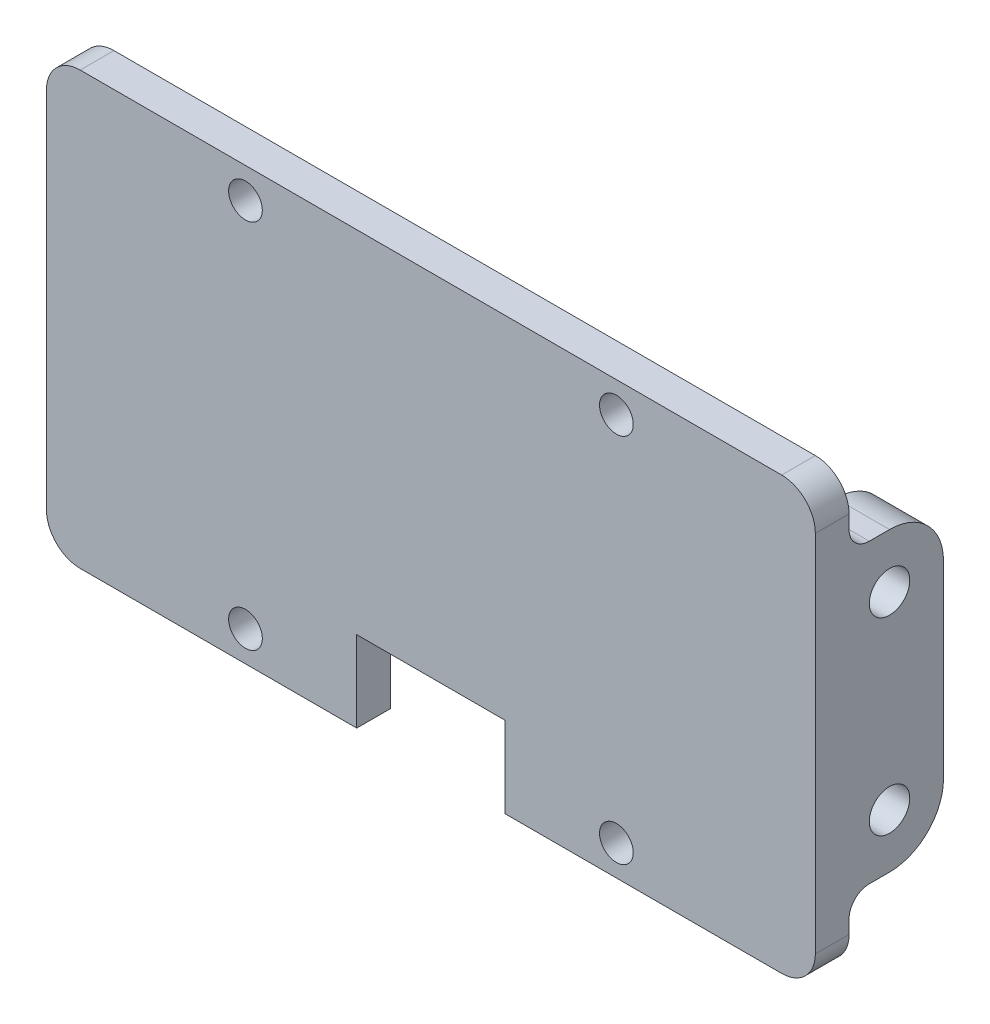
SolidWorks part; units mm, degrees
ref_plane "前视基准面" through (0, 0, 0) normal (0, 0, 1) x (1, 0, 0)
ref_plane "上视基准面" through (0, 0, 0) normal (0, 1, 0) x (1, 0, 0)
ref_plane "右视基准面" through (0, 0, 0) normal (1, 0, 0) x (0, 0, -1)
sketch "草图1" plane through (0, 0, 0) normal (0, 0, 1) x (1, 0, 0)
  line L1 (-16, -16) -> (16, -16)
  line L3 (-16, 16) -> (16, 16)
  line L13 (0, -10) -> (5.5, -10)
  line L14 (5.5, -10) -> (5.5, -16)
  line L15 (5.5, -16) -> (-5.5, -16)
  line L16 (-5.5, -16) -> (-5.5, -10)
  line L17 (-5.5, -10) -> (0, -10)
  line L18 (-28.5, -16) -> (28.5, -16)
  line L19 (-28.5, -16) -> (-28.5, 16)
  line L20 (-28.5, 16) -> (28.5, 16)
  line L21 (28.5, -16) -> (28.5, 16)
  circle A0 centre (-13.75, 13.75) radius 1.25
  circle A1 centre (13.75, 13.75) radius 1.25
  circle A2 centre (-13.75, -13.75) radius 1.25
  circle A3 centre (13.75, -13.75) radius 1.25
  point P0 (0, 0)
  point P6 (0, 0)
  point P15 (0, 0)
extrude "凸台-拉伸1" add sketch "草图1" along normal blind 2.5
sketch "草图3" plane through (-28.5, 0, 0) normal (-1, 0, 0) x (0, 0, 1)
  line L2 (0, -16) -> (0, 16) construction
  line L8 (-3, 11) -> (0, 11)
  line L10 (-7, -7) -> (-7, 7)
  line L11 (-3, -11) -> (0, -11)
  line L12 (0, -11) -> (0, 11)
  circle A0 centre (-3, 7) radius 1.5
  circle A1 centre (-3, -7) radius 1.5
  arc A4 (-7, 7) -> (-3, 11) centre (-3, 7) cw
  arc A5 (-7, -7) -> (-3, -11) centre (-3, -7) ccw
extrude "凸台-拉伸2" add sketch "草图3" against normal blind 4
sketch "草图4" plane through (28.5, 0, 0) normal (1, 0, 0) x (0, 0, -1)
  line L16 (7, -7) -> (7, 7)
  line L17 (3, 11) -> (0, 11)
  line L18 (0, 11) -> (0, -11)
  line L19 (0, -11) -> (3, -11)
  line L20 (7, -7) -> (7, 7)
  line L21 (3, 11) -> (0, 11)
  line L22 (0, 11) -> (0, -11)
  line L23 (0, -11) -> (3, -11)
  circle A9 centre (3, 7) radius 1.5
  circle A10 centre (3, 7) radius 1.5
  circle A11 centre (3, -7) radius 1.5
  circle A12 centre (3, -7) radius 1.5
  arc A14 (3, -11) -> (7, -7) centre (3, -7) ccw
  arc A15 (7, 7) -> (3, 11) centre (3, 7) ccw
  arc A16 (3, -11) -> (7, -7) centre (3, -7) ccw
  arc A17 (7, 7) -> (3, 11) centre (3, 7) ccw
  point P9 (0, 0)
  dimension "D1" = 0
  dimension "D2" = 0
  dimension "D3" = 0
extrude "凸台-拉伸3" add sketch "草图4" against normal blind 4
fillet "圆角2" radius 2.5 4 edges at (-28.5, -16, 1.25) (28.5, -16, 1.25) (-28.5, 16, 1.25) (28.5, 16, 1.25)
fillet "圆角3" radius 1.5 4 edges at (26.5, 11, 0) (26.5, -11, 0) (-26.5, -11, 0) (-26.5, 11, 0)
other "角撑板1" parameters "D1"=5, "D2"=5, "D3"=0, "D4"=0, "D10"=5, "D11"=7, "D12"=7, "D13"=15, "D14"=45, "D15"=15
sketch "草图6" plane through (24.5, 0, 0) normal (0, 1, 0) x (1, 0, 0)
  line L0 (0, 0) -> (0, 7)
  line L1 (0, 0) -> (-7, 0)
  line L2 (0, 7) -> (-7, 0)
other "角撑板2" parameters "D1"=5, "D2"=5, "D3"=0, "D4"=0, "D10"=5, "D11"=7, "D12"=7, "D13"=15, "D14"=45, "D15"=15
sketch "草图7" plane through (-24.5, 0, 0) normal (0, 1, 0) x (1, 0, 0)
  line L0 (0, 0) -> (7, 0)
  line L1 (0, 0) -> (0, 7)
  line L2 (7, 0) -> (0, 7)
